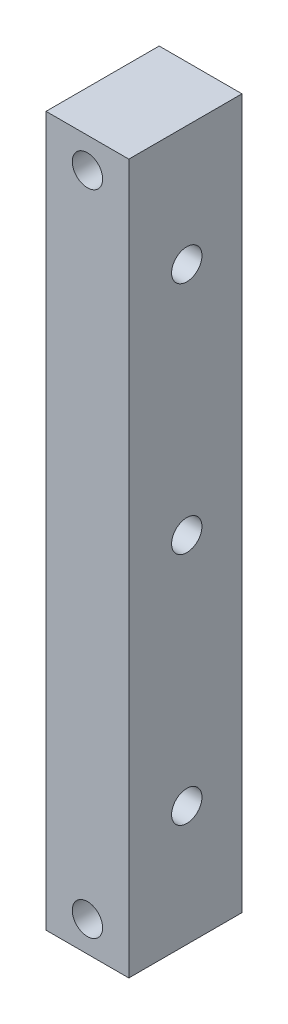
SolidWorks part; units mm, degrees
other "Outlet Housing Reaction Block"
ref_plane "Front Plane" through (0, 0, 0) normal (0, 0, 1) x (1, 0, 0)
ref_plane "Top Plane" through (0, 0, 0) normal (0, 1, 0) x (1, 0, 0)
ref_plane "Right Plane" through (0, 0, 0) normal (1, 0, 0) x (0, 0, -1)
sketch3d "Block outline datum points"
  point P0 (-66.2917, -54.7, 11)
  point P1 (-56.2917, -54.7, 11)
  point P2 (-66.2917, -44.7, 11)
ref_plane "Block outline plane" through (0, 0, 11) normal (0, 0, 1) x (1, 0, 0)
sketch "Block outline" plane through (0, 0, 11) normal (0, 0, 1) x (1, 0, 0)
  line L0 (-66.2917, -54.7) -> (-60.2917, -54.7)
  line L1 (-60.2917, -54.7) -> (-60.2917, -3.3)
  line L2 (-60.2917, -3.3) -> (-66.2917, -3.3)
  line L3 (-66.2917, -3.3) -> (-66.2917, -54.7)
extrude "Reaction block thickness" add sketch "Block outline" along normal blind 8.2 separate body
sketch3d "Lane 1 inner cable clearance profile datum points"
  point P0 (-66.3917, -12, 15)
  point P1 (-66.3917, -2, 15)
  point P2 (-66.3917, -12, 25)
ref_plane "Lane 1 inner cable clearance profile plane" through (-66.3917, 0, 0) normal (1, 0, 0) x (0, 0, -1)
sketch "Lane 1 inner cable clearance profile" plane through (-66.3917, 0, 0) normal (1, 0, 0) x (0, 0, -1)
  circle A0 centre (-15, -12) radius 1.1
extrude "Lane 1 inner cable clearance" cut sketch "Lane 1 inner cable clearance profile" along normal blind 6.2
sketch3d "Lane 1 compression housing socket profile datum points"
  point P0 (-66.3917, -12, 15)
  point P1 (-66.3917, -2, 15)
  point P2 (-66.3917, -12, 25)
ref_plane "Lane 1 compression housing socket profile plane" through (-66.3917, 0, 0) normal (1, 0, 0) x (0, 0, -1)
sketch "Lane 1 compression housing socket profile" plane through (-66.3917, 0, 0) normal (1, 0, 0) x (0, 0, -1)
  circle A0 centre (-15, -12) radius 2.05
extrude "Lane 1 compression housing socket" cut sketch "Lane 1 compression housing socket profile" along normal blind 4.1
sketch3d "Lane 2 inner cable clearance profile datum points"
  point P0 (-66.3917, -29, 15)
  point P1 (-66.3917, -19, 15)
  point P2 (-66.3917, -29, 25)
ref_plane "Lane 2 inner cable clearance profile plane" through (-66.3917, 0, 0) normal (1, 0, 0) x (0, 0, -1)
sketch "Lane 2 inner cable clearance profile" plane through (-66.3917, 0, 0) normal (1, 0, 0) x (0, 0, -1)
  circle A0 centre (-15, -29) radius 1.1
extrude "Lane 2 inner cable clearance" cut sketch "Lane 2 inner cable clearance profile" along normal blind 6.2
sketch3d "Lane 2 compression housing socket profile datum points"
  point P0 (-66.3917, -29, 15)
  point P1 (-66.3917, -19, 15)
  point P2 (-66.3917, -29, 25)
ref_plane "Lane 2 compression housing socket profile plane" through (-66.3917, 0, 0) normal (1, 0, 0) x (0, 0, -1)
sketch "Lane 2 compression housing socket profile" plane through (-66.3917, 0, 0) normal (1, 0, 0) x (0, 0, -1)
  circle A0 centre (-15, -29) radius 2.05
extrude "Lane 2 compression housing socket" cut sketch "Lane 2 compression housing socket profile" along normal blind 4.1
sketch3d "Lane 3 inner cable clearance profile datum points"
  point P0 (-66.3917, -46, 15)
  point P1 (-66.3917, -36, 15)
  point P2 (-66.3917, -46, 25)
ref_plane "Lane 3 inner cable clearance profile plane" through (-66.3917, 0, 0) normal (1, 0, 0) x (0, 0, -1)
sketch "Lane 3 inner cable clearance profile" plane through (-66.3917, 0, 0) normal (1, 0, 0) x (0, 0, -1)
  circle A0 centre (-15, -46) radius 1.1
extrude "Lane 3 inner cable clearance" cut sketch "Lane 3 inner cable clearance profile" along normal blind 6.2
sketch3d "Lane 3 compression housing socket profile datum points"
  point P0 (-66.3917, -46, 15)
  point P1 (-66.3917, -36, 15)
  point P2 (-66.3917, -46, 25)
ref_plane "Lane 3 compression housing socket profile plane" through (-66.3917, 0, 0) normal (1, 0, 0) x (0, 0, -1)
sketch "Lane 3 compression housing socket profile" plane through (-66.3917, 0, 0) normal (1, 0, 0) x (0, 0, -1)
  circle A0 centre (-15, -46) radius 2.05
extrude "Lane 3 compression housing socket" cut sketch "Lane 3 compression housing socket profile" along normal blind 4.1
sketch3d "M2 fixing clearance 1 profile datum points"
  point P0 (-63.2917, -5.5, 10.9)
  point P1 (-53.2917, -5.5, 10.9)
  point P2 (-63.2917, 4.5, 10.9)
ref_plane "M2 fixing clearance 1 profile plane" through (0, 0, 10.9) normal (0, 0, 1) x (1, 0, 0)
sketch "M2 fixing clearance 1 profile" plane through (0, 0, 10.9) normal (0, 0, 1) x (1, 0, 0)
  circle A0 centre (-63.2917, -5.5) radius 1.1
extrude "M2 fixing clearance 1" cut sketch "M2 fixing clearance 1 profile" along normal blind 8.4
sketch3d "M2 fixing clearance 2 profile datum points"
  point P0 (-63.2917, -52.5, 10.9)
  point P1 (-53.2917, -52.5, 10.9)
  point P2 (-63.2917, -42.5, 10.9)
ref_plane "M2 fixing clearance 2 profile plane" through (0, 0, 10.9) normal (0, 0, 1) x (1, 0, 0)
sketch "M2 fixing clearance 2 profile" plane through (0, 0, 10.9) normal (0, 0, 1) x (1, 0, 0)
  circle A0 centre (-63.2917, -52.5) radius 1.1
extrude "M2 fixing clearance 2" cut sketch "M2 fixing clearance 2 profile" along normal blind 8.4
